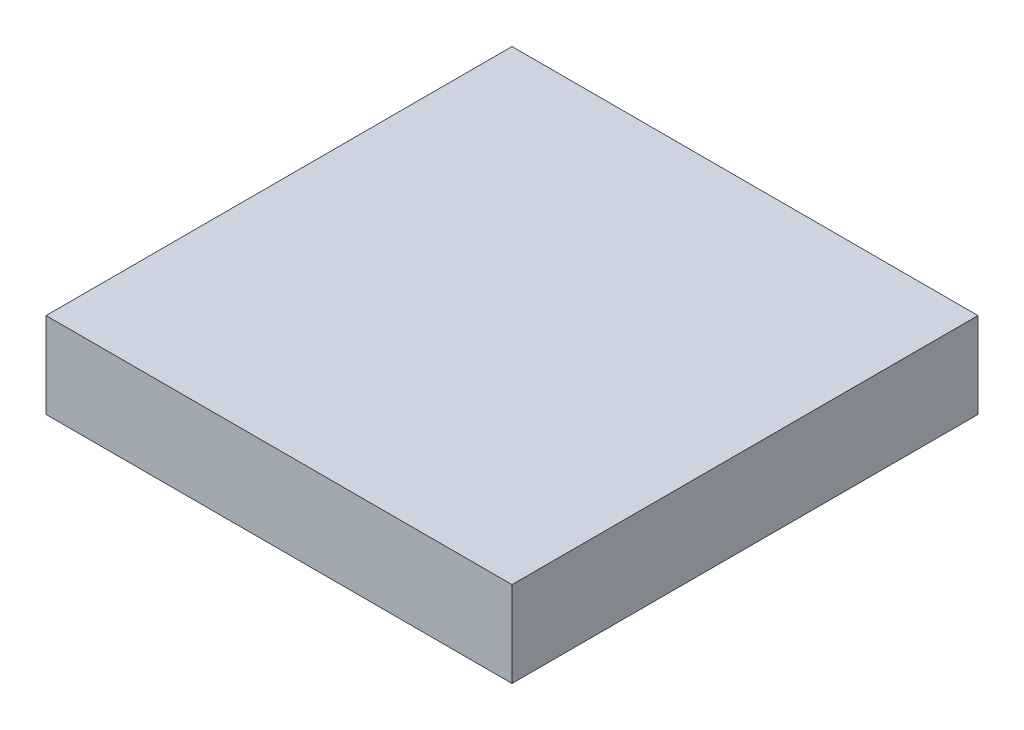
SolidWorks part; units mm, degrees
ref_plane "前视基准面" through (0, 0, 0) normal (0, 0, 1) x (1, 0, 0)
ref_plane "上视基准面" through (0, 0, 0) normal (0, 1, 0) x (1, 0, 0)
ref_plane "右视基准面" through (0, 0, 0) normal (1, 0, 0) x (0, 0, -1)
other "Configuration Table"
sketch "草图1" plane through (0, 0, 0) normal (0, 1, 0) x (1, 0, 0)
  line L1 (-7.62, -7.62) -> (7.62, -7.62)
  line L2 (-7.62, -7.62) -> (-7.62, 7.62)
  line L3 (-7.62, 7.62) -> (7.62, 7.62)
  line L4 (7.62, -7.62) -> (7.62, 7.62)
  line L5 (-7.62, -7.62) -> (7.62, 7.62) construction
  line L6 (-7.62, 7.62) -> (7.62, -7.62) construction
  point P0 (0, 0)
  dimension "D1" = 15.24
  dimension "D2" = 15.24
extrude "凸台-拉伸1" add sketch "草图1" along normal blind 2.8
